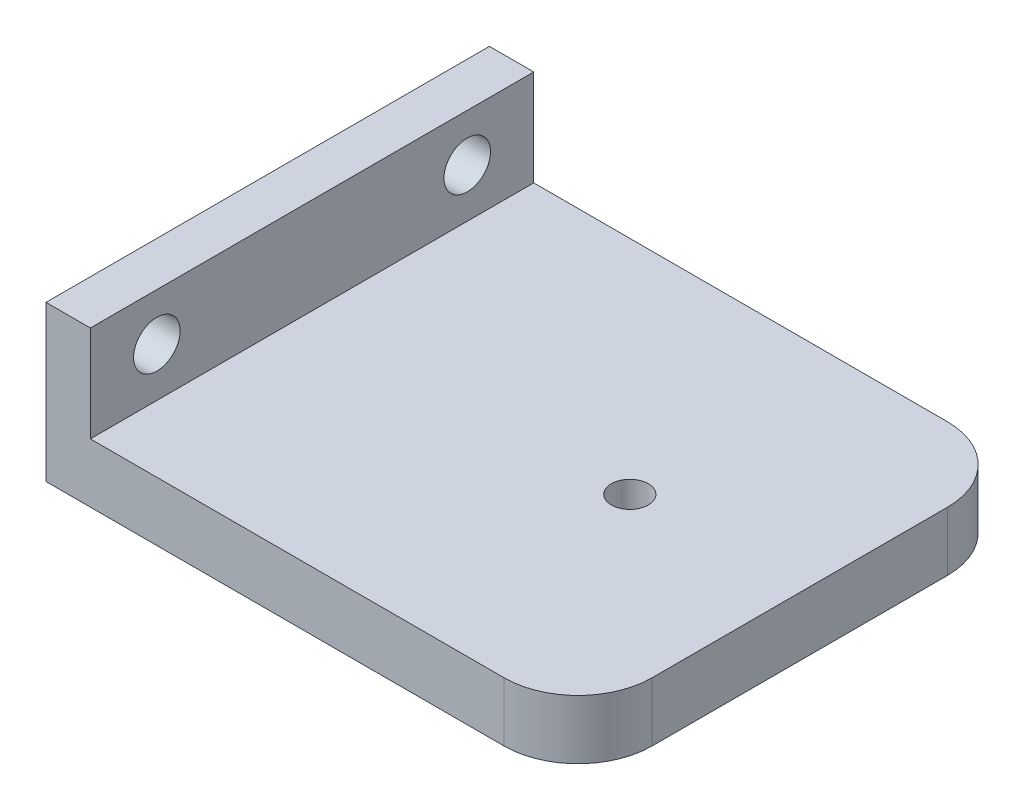
SolidWorks part; units mm, degrees
material "Du"
ref_plane "Front Plane" through (0, 0, 0) normal (0, 0, 1) x (1, 0, 0)
ref_plane "Top Plane" through (0, 0, 0) normal (0, 1, 0) x (1, 0, 0)
ref_plane "Right Plane" through (0, 0, 0) normal (1, 0, 0) x (0, 0, -1)
sketch "Sketch1" plane through (0, 0, 0) normal (1, 0, 0) x (0, 0, -1)
  line L1 (-15, -5.25) -> (15, -5.25)
  line L2 (-15, -5.25) -> (-15, 5.25)
  line L3 (-15, 5.25) -> (15, 5.25)
  line L4 (15, -5.25) -> (15, 5.25)
  line L5 (-15, -5.25) -> (15, 5.25) construction
  line L6 (-15, 5.25) -> (15, -5.25) construction
  point P0 (0, 0)
  dimension "D1" = 30
  dimension "D2" = 10.5
extrude "Boss-Extrude1" add sketch "Sketch1" along normal blind 3
sketch "Sketch2" plane through (3, 0, 0) normal (1, 0, 0) x (0, 0, -1)
  line L0 (15, -5.25) -> (15, 5.25) construction
  line L1 (-15, -5.25) -> (15, -5.25)
  line L2 (-15, -5.25) -> (-15, -1.25)
  line L3 (-15, -1.25) -> (15, -1.25)
  line L4 (15, -5.25) -> (15, -1.25)
  dimension "D1" = 30
  dimension "D2" = 4
extrude "Boss-Extrude2" add sketch "Sketch2" along normal blind 33
fillet "Fillet1" radius 5 2 edges at (36, -3.25, -15) (36, -3.25, 15)
sketch "Sketch3" plane through (3, 0, 0) normal (1, 0, 0) x (0, 0, -1)
  line L0 (15, 5.25) -> (-15, 5.25) construction
  line L1 (-15, 5.25) -> (-15, -1.25) construction
  circle A0 centre (-10.5, 2.05) radius 1.575
  dimension "D1" = 3.15
  dimension "D2" = 3.2
  dimension "D3" = 4.5
extrude "Cut-Extrude1" cut sketch "Sketch3" against normal through all
sketch "Sketch4" plane through (3, 0, 0) normal (1, 0, 0) x (0, 0, -1)
  line L0 (15, 5.25) -> (-15, 5.25) construction
  line L1 (15, -1.25) -> (15, 5.25) construction
  circle A0 centre (10.5, 2.05) radius 1.575
  dimension "D1" = 3.15
  dimension "D2" = 3.2
  dimension "D3" = 4.5
extrude "Cut-Extrude2" cut sketch "Sketch4" against normal through all
sketch "Sketch5" plane through (0, -5.25, 0) normal (0, -1, 0) x (-1, 0, 0)
  line L0 (-5.775, 0) -> (5.775, 0) construction
  line L1 (-36, -10) -> (-36, 10) construction
  circle A0 centre (-24.5, 0) radius 1.25
  dimension "D1" = 2.5
  dimension "D2" = 11.5
extrude "Cut-Extrude3" cut sketch "Sketch5" against normal through all
